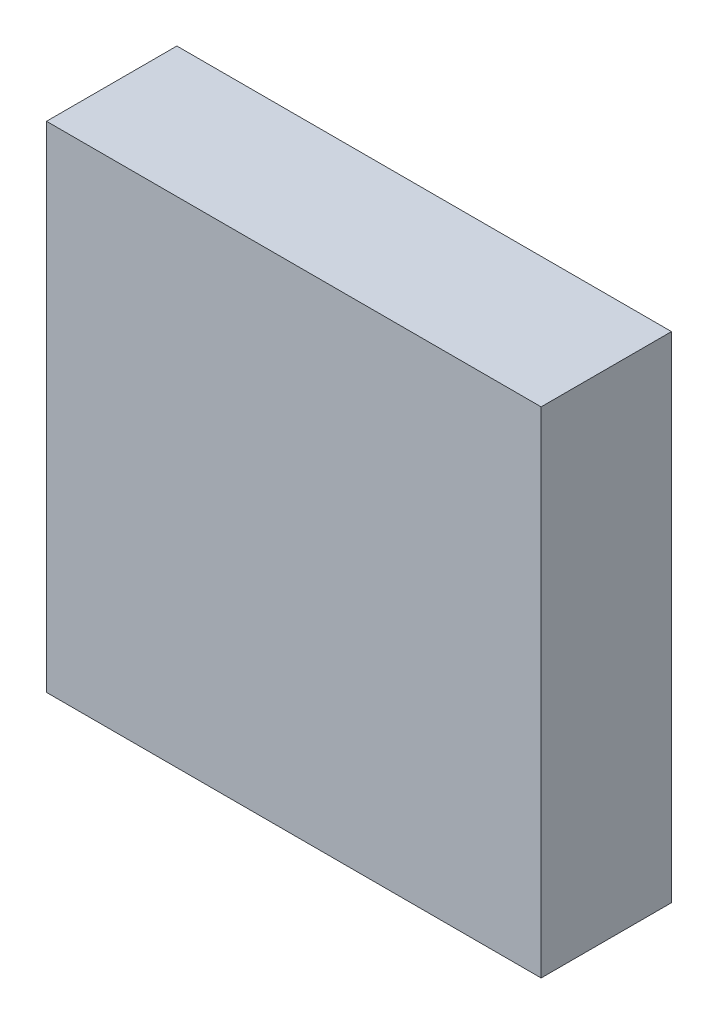
SolidWorks part; units mm, degrees
ref_plane "Front Plane" through (0, 0, 0) normal (0, 0, 1) x (1, 0, 0)
ref_plane "Top Plane" through (0, 0, 0) normal (0, 1, 0) x (1, 0, 0)
ref_plane "Right Plane" through (0, 0, 0) normal (1, 0, 0) x (0, 0, -1)
sketch "Sketch1" plane through (0, 0, 0) normal (0, 0, 1) x (1, 0, 0)
  line L0 (0, 3.7941) -> (3.7941, 3.7941)
  line L1 (3.7941, 3.7941) -> (3.7941, 0)
  line L2 (3.7941, 0) -> (0, 0)
  line L3 (0, 0) -> (0, 3.7941)
extrude "Component_Outline" add sketch "Sketch1" along normal blind 1 separate body
sketch3d "3DSketch1"
  line L0 (0, 0, 0) -> (1, 0, 0)
  line L1 (0, 0, 0) -> (0, 1, 0)
  line L2 (0, 0, 0) -> (0, 0, 1)
  point P0 (0, 0, 0)
